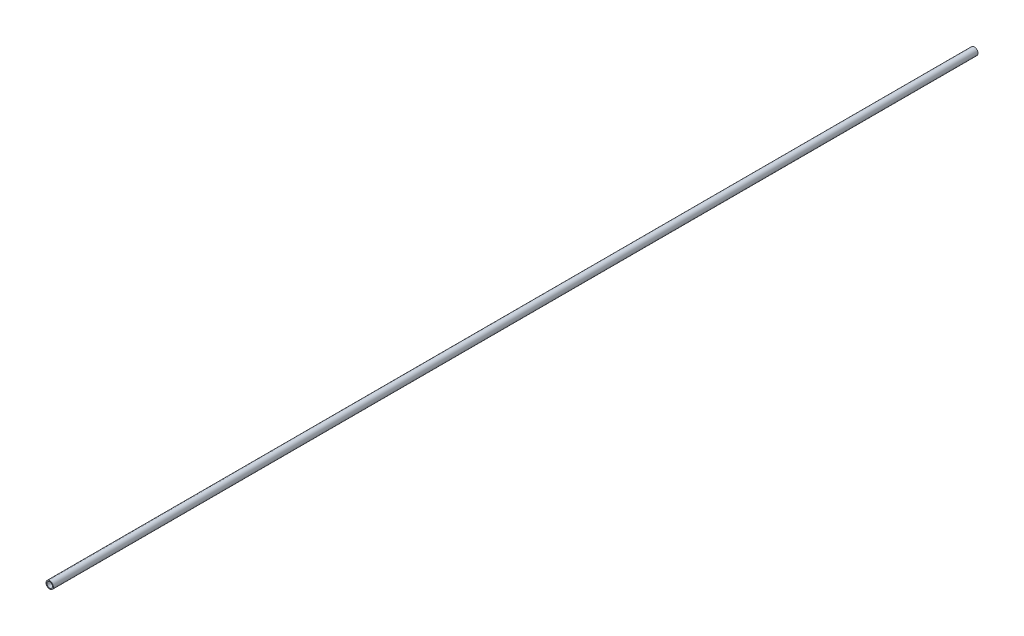
SolidWorks part; units mm, degrees
material "Poltrusion Carbon Fiber"
ref_plane "Front Plane" through (0, 0, 0) normal (0, 0, 1) x (1, 0, 0)
ref_plane "Top Plane" through (0, 0, 0) normal (0, 1, 0) x (1, 0, 0)
ref_plane "Right Plane" through (0, 0, 0) normal (1, 0, 0) x (0, 0, -1)
sketch "Эскиз1" plane through (0, 0, 0) normal (0, 0, 1) x (1, 0, 0)
  circle A0 centre (0, 0) radius 4
  circle A1 centre (0, 0) radius 3
  dimension "D1" = 8
  dimension "D2" = 1
extrude "Бобышка-Вытянуть1" add sketch "Эскиз1" along normal mid plane 1000
